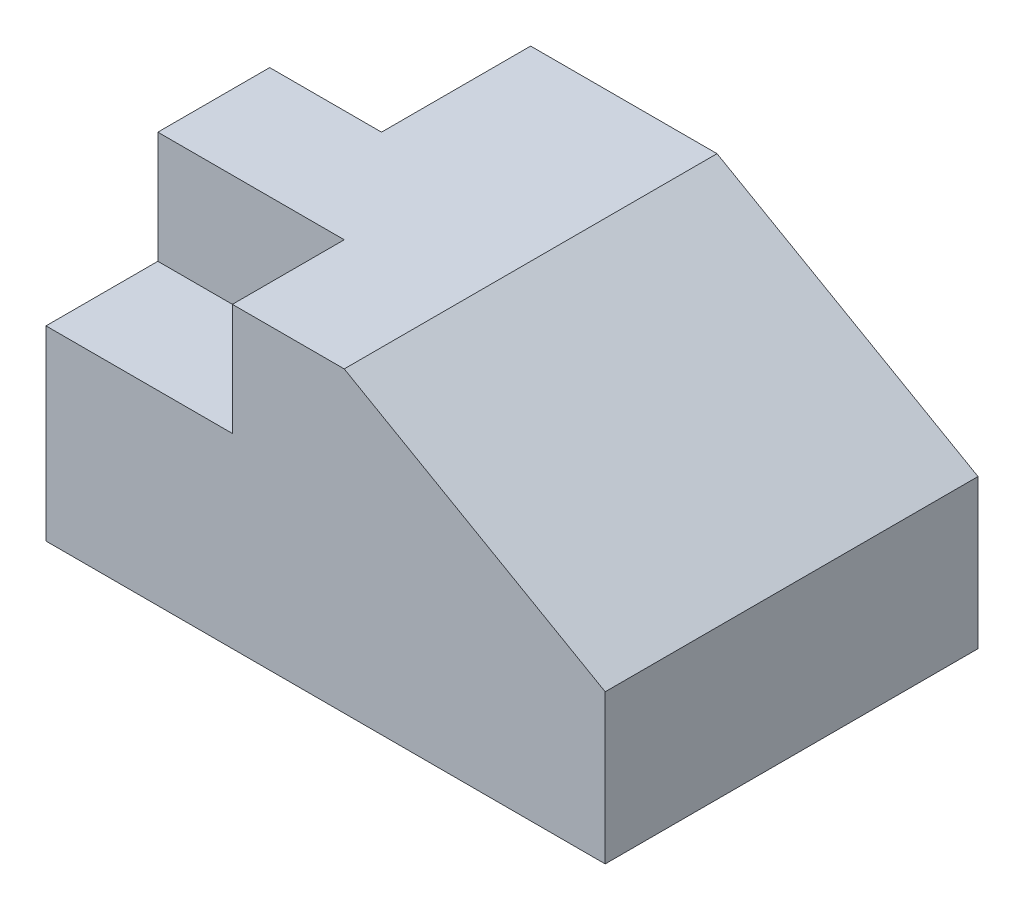
SolidWorks part; units mm, degrees
ref_plane "Front Plane" through (0, 0, 0) normal (0, 0, 1) x (1, 0, 0)
ref_plane "Top Plane" through (0, 0, 0) normal (0, 1, 0) x (1, 0, 0)
ref_plane "Right Plane" through (0, 0, 0) normal (1, 0, 0) x (0, 0, -1)
sketch "Sketch1" plane through (0, 0, 0) normal (0, 0, 1) x (1, 0, 0)
  line L0 (0, 0) -> (150, 0)
  line L1 (150, 0) -> (150, 40)
  line L2 (150, 40) -> (80, 80)
  line L3 (80, 80) -> (0, 80)
  line L4 (0, 80) -> (0, 0)
  point P3 (150, 25.9311)
  dimension "D1" = 150
  dimension "D2" = 80
  dimension "D3" = 80
  dimension "D4" = 40
extrude "Boss-Extrude1" add sketch "Sketch1" against normal blind 100
sketch "Sketch2" plane through (0, 80, 0) normal (0, 1, 0) x (1, 0, 0)
  line L1 (0, 0) -> (50, 0)
  line L2 (0, 0) -> (0, 30)
  line L3 (0, 30) -> (50, 30)
  line L4 (50, 0) -> (50, 30)
  line L5 (0, 100) -> (30, 100)
  line L6 (0, 100) -> (0, 60)
  line L7 (0, 60) -> (30, 60)
  line L8 (30, 100) -> (30, 60)
  dimension "D1" = 30
  dimension "D2" = 50
  dimension "D3" = 30
  dimension "D4" = 40
extrude "Cut-Extrude1" cut sketch "Sketch2" against normal blind 30
